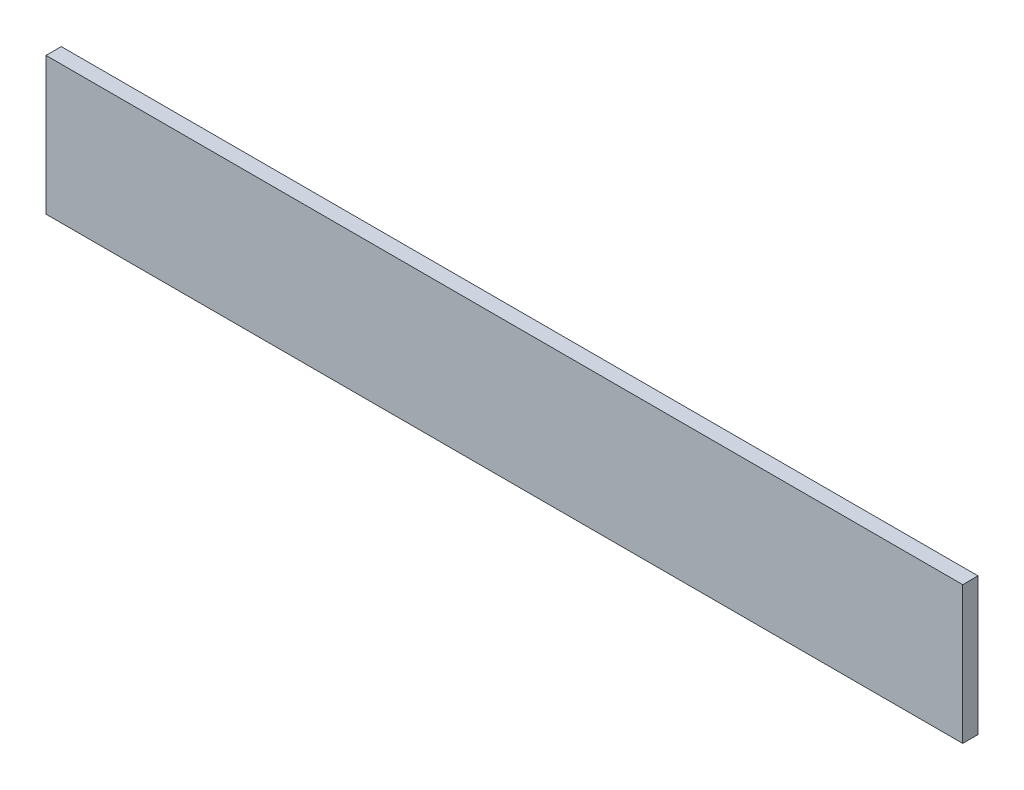
SolidWorks part; units mm, degrees
ref_plane "Front Plane" through (0, 0, 0) normal (0, 0, 1) x (1, 0, 0)
ref_plane "Top Plane" through (0, 0, 0) normal (0, 1, 0) x (1, 0, 0)
ref_plane "Right Plane" through (0, 0, 0) normal (1, 0, 0) x (0, 0, -1)
sketch "Sketch1" plane through (0, 0, 0) normal (0, 0, 1) x (1, 0, 0)
  line L1 (0, 0) -> (300, 0)
  line L2 (0, 0) -> (0, -45)
  line L3 (0, -45) -> (300, -45)
  line L4 (300, 0) -> (300, -45)
  dimension "D1" = 300
  dimension "D2" = 45
extrude "Boss-Extrude1" add sketch "Sketch1" along normal blind 5
